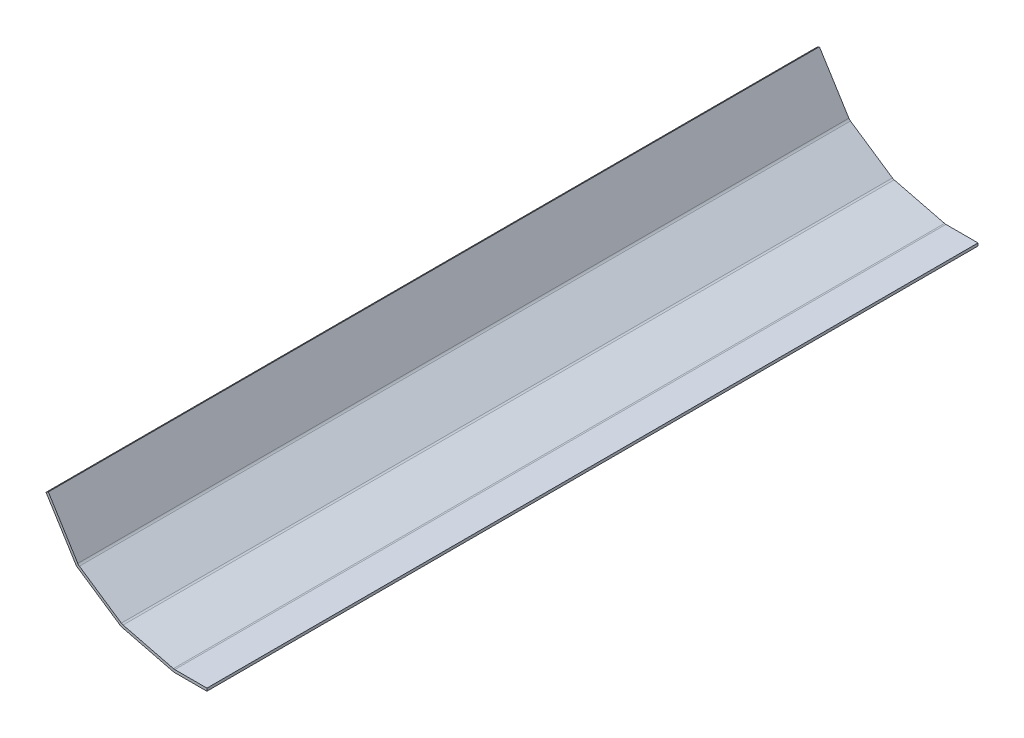
SolidWorks part; units mm, degrees
ref_plane "Front Plane" through (0, 0, 0) normal (0, 0, 1) x (1, 0, 0)
ref_plane "Top Plane" through (0, 0, 0) normal (0, 1, 0) x (1, 0, 0)
ref_plane "Right Plane" through (0, 0, 0) normal (1, 0, 0) x (0, 0, -1)
sketch "Continuous outer impact skin profile" plane through (0, 0, 0) normal (0, 0, 1) x (1, 0, 0)
  line L0 (152, 3) -> (140.2456, 3)
  line L1 (139.7617, 3.0594) -> (121.3422, 7.6519)
  line L2 (120.7076, 7.9344) -> (105.3524, 18.2916)
  line L3 (104.7747, 18.8899) -> (94, 36.133)
  line L4 (94, 36.133) -> (93.152, 35.6031)
  line L5 (93.152, 35.6031) -> (103.9267, 18.36)
  line L6 (104.7932, 17.4626) -> (120.1484, 7.1054)
  line L7 (121.1003, 6.6816) -> (139.5198, 2.0891)
  line L8 (140.2456, 2) -> (152, 2)
  line L9 (152, 2) -> (152, 3)
  arc A0 (140.2456, 3) -> (139.7617, 3.0594) centre (140.2456, 5) cw
  arc A1 (121.3422, 7.6519) -> (120.7076, 7.9344) centre (121.826, 9.5925) cw
  arc A2 (105.3524, 18.2916) -> (104.7747, 18.8899) centre (106.4708, 19.9497) cw
  arc A3 (103.9267, 18.36) -> (104.7932, 17.4626) centre (106.4708, 19.9497) ccw
  arc A4 (120.1484, 7.1054) -> (121.1003, 6.6816) centre (121.826, 9.5925) ccw
  arc A5 (139.5198, 2.0891) -> (140.2456, 2) centre (140.2456, 5) ccw
extrude "Continuous outer impact skin" add sketch "Continuous outer impact skin profile" along normal blind 282
